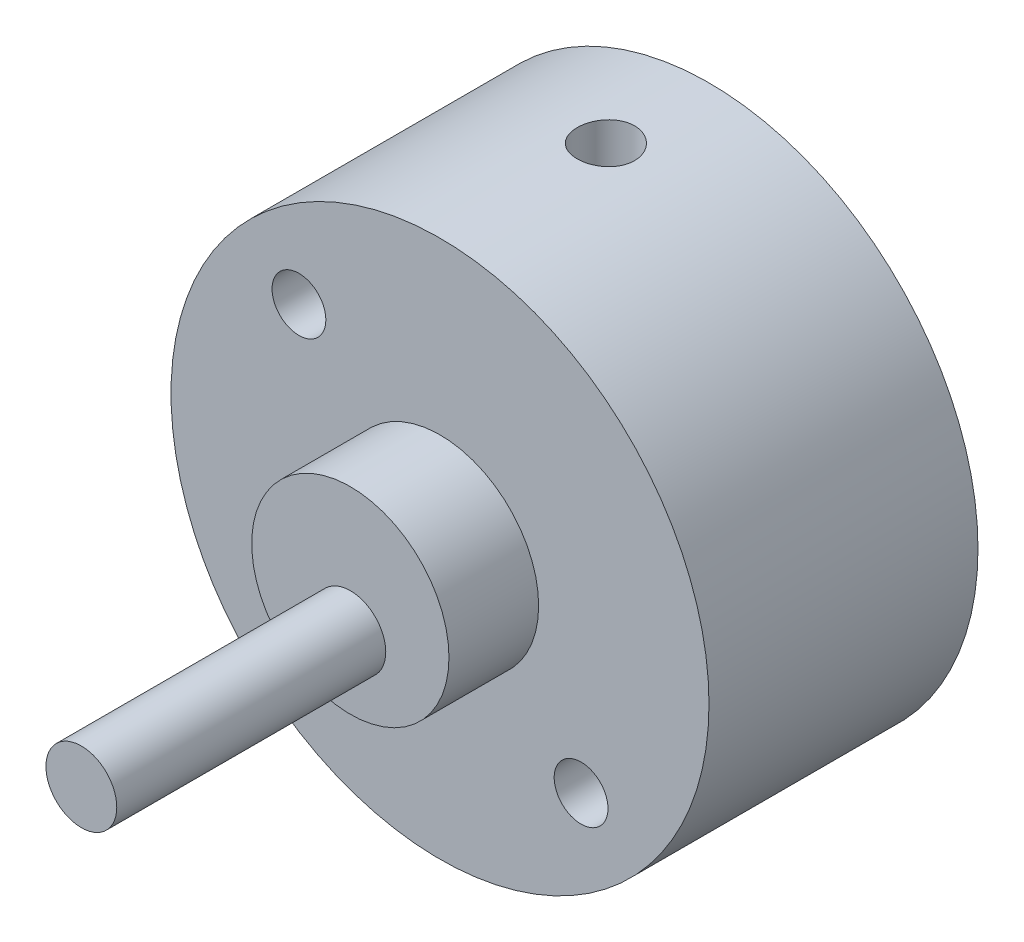
SolidWorks part; units mm, degrees
material "ABS"
ref_plane "Front Plane" through (0, 0, 0) normal (0, 0, 1) x (1, 0, 0)
ref_plane "Top Plane" through (0, 0, 0) normal (0, 1, 0) x (1, 0, 0)
ref_plane "Right Plane" through (0, 0, 0) normal (1, 0, 0) x (0, 0, -1)
sketch "Sketch1" plane through (0, 0, 0) normal (0, 0, 1) x (1, 0, 0)
  circle A0 centre (0, 0) radius 30
  circle A1 centre (0, 0) radius 20
  circle A2 centre (0, 0) radius 10.35
  dimension "D1" = 60
  dimension "D2" = 40
  dimension "D3" = 20.7
extrude "Boss-Extrude1" add sketch "Sketch1" along normal blind 30 contours A0
sketch "Sketch2" plane through (0, 0, 30) normal (0, 0, 1) x (1, 0, 0)
  circle A0 centre (0, 0) radius 11
  dimension "D1" = 22
sketch "Sketch5" plane through (0, 0, 30) normal (0, 0, 1) x (1, 0, 0)
  line L0 (0, 0) -> (0, 66.1073) construction
  line L1 (-5.7455, 0) -> (-60.7604, 0) construction
  line L2 (0, 0) -> (-38.8576, 38.8576) construction
  circle A0 centre (0, 0) radius 22.25 construction
  point P8 (-15.7331, 15.7331)
  point P10 (15.7331, -15.7331)
  point P15 (-15.7331, -15.7331)
  dimension "D1" = 45
hole_wizard "Ø6.0mm Dowel Hole1" positions "Sketch7" profile "Sketch6" hole size "Ø6.0" standard "ANSI Metric" end condition up to next
sketch "Sketch7" plane through (0, 0, 30) normal (0, 0, 1) x (1, 0, 0)
  point P0 (-15.7331, 15.7331)
  point P3 (15.7331, -15.7331)
  point P6 (-15.7331, -15.7331)
sketch "Sketch6" plane through (-15.7331, 15.7331, 30) normal (1, 0, 0) x (0, -1, 0)
  line L0 (0, 0) -> (0, 30)
  line L1 (0, 30) -> (3, 30)
  line L2 (3, 30) -> (3, 0)
  line L5 (3, 0) -> (0, 0)
  line L11 (0, -6.35) -> (0, 107.95) construction
  dimension "Thru Hole Dia." = 6
  dimension "Thru Hole Depth" = 30
extrude "Boss-Extrude2" add sketch "Sketch2" along normal blind 10
sketch "Sketch9" plane through (0, 0, 40) normal (0, 0, 1) x (1, 0, 0)
  line L2 (0, -200000) -> (0, 200066.1073) construction
  circle A0 centre (0, -3) radius 3.95
  point P0 (0, -3)
  dimension "D2" = 7.9
  dimension "D1" = 3
extrude "Boss-Extrude3" add sketch "Sketch9" along normal blind 30
sketch "Sketch10" plane through (0, 0, 0) normal (0, 0, -1) x (-1, 0, 0)
  circle A1 centre (0, 0) radius 10.25
  dimension "D2" = 20.5
extrude "Cut-Extrude2" cut sketch "Sketch10" against normal blind 20.5
ref_plane "Plane2" through (0, 30, 0) normal (0, 1, 0) x (1, 0, 0)
sketch "Sketch12" plane through (0, 30, 0) normal (0, 1, 0) x (1, 0, 0)
  line L0 (10.25, 0) -> (-10.25, 0) construction
  circle A0 centre (0, -11.5) radius 3.2
  point P0 (0, -20.5)
  point P3 (0, -11.5)
  dimension "D3" = 6.4
  dimension "D1" = 20.5
  dimension "D2" = 9
extrude "Cut-Extrude3" cut sketch "Sketch12" against normal blind 70
